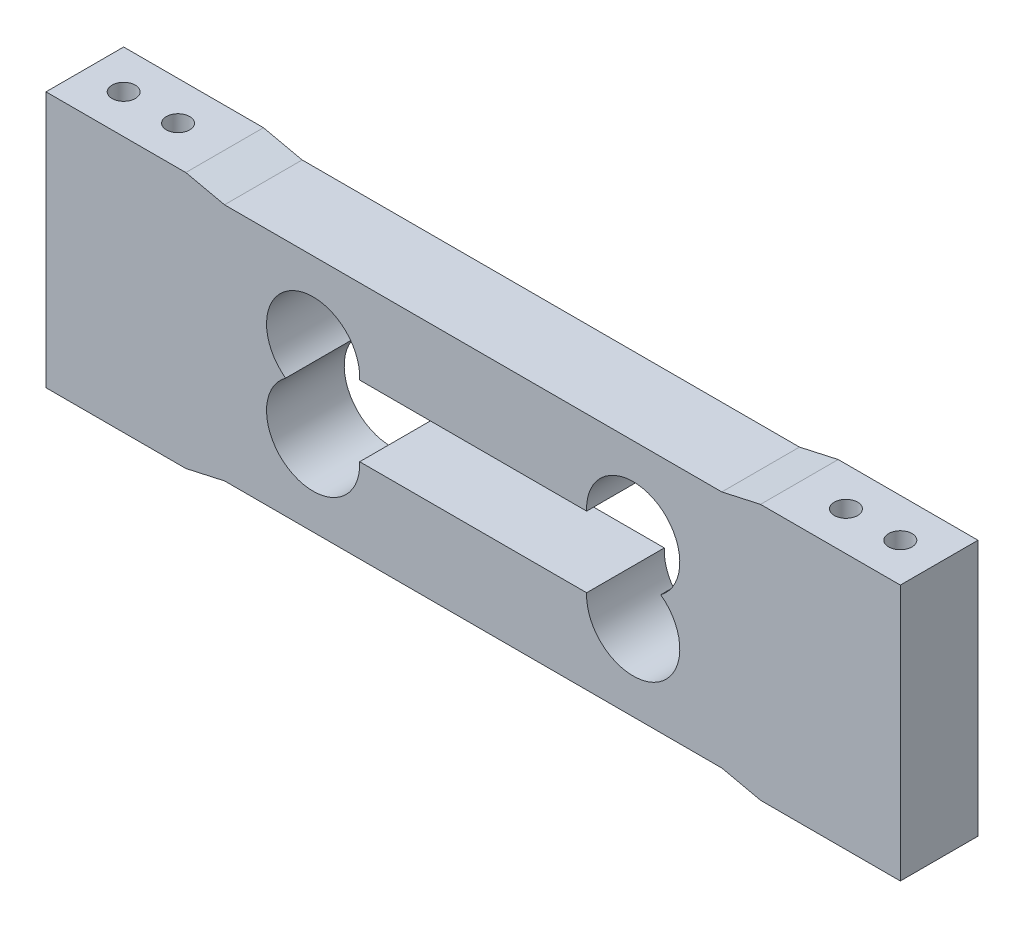
SolidWorks part; units mm, degrees
ref_plane "Front Plane" through (0, 0, 0) normal (0, 0, 1) x (1, 0, 0)
ref_plane "Top Plane" through (0, 0, 0) normal (0, 1, 0) x (1, 0, 0)
ref_plane "Right Plane" through (0, 0, 0) normal (1, 0, 0) x (0, 0, -1)
sketch "Sketch1" plane through (0, 0, 0) normal (0, 0, 1) x (1, 0, 0)
  line L0 (-55, 16.5) -> (-37, 16.5)
  line L1 (-37, 16.5) -> (-32.0158, 15.3954)
  line L2 (-32.0158, 15.3954) -> (32.0158, 15.3954)
  line L3 (32.0158, 15.3954) -> (37, 16.5)
  line L4 (37, 16.5) -> (55, 16.5)
  line L5 (55, 16.5) -> (55, -16.5)
  line L6 (55, -16.5) -> (37, -16.5)
  line L7 (37, -16.5) -> (32.0158, -15.3954)
  line L8 (32.0158, -15.3954) -> (-32.0158, -15.3954)
  line L9 (-32.0158, -15.3954) -> (-37, -16.5)
  line L10 (-37, -16.5) -> (-55, -16.5)
  line L11 (-55, -16.5) -> (-55, 16.5)
  line L12 (0, 15.3954) -> (0, -15.3954) construction
  line L13 (-55, 0) -> (55, 0) construction
  line L14 (-14.6102, 4.5503) -> (14.6102, 4.5503)
  line L15 (-14.6102, -4.5503) -> (14.6102, -4.5503)
  arc A0 (14.6102, 4.5503) -> (24.1514, 0) centre (20.6033, 4.8385) cw
  arc A1 (14.6102, -4.5503) -> (24.1514, 0) centre (20.6033, -4.8385) ccw
  arc A2 (-14.6102, -4.5503) -> (-24.1514, 0) centre (-20.6033, -4.8385) cw
  arc A3 (-14.6102, 4.5503) -> (-24.1514, 0) centre (-20.6033, 4.8385) ccw
  point P14 (0, 0)
  point P20 (-20.3383, 0)
  point P21 (-14.2938, -9.1795)
  point P24 (0, 4.5503)
  point P30 (0, -4.5503)
  point P31 (-20.6262, 0)
  point P32 (-16.8843, -9.947)
  point P33 (0, 0)
  point P34 (-10.456, 7.8988)
  point P36 (0, 3.6258)
  point P37 (14.6102, 4.8385)
  dimension "D1" = 33
  dimension "D2" = 18
  dimension "D3" = 74
  dimension "D4" = 110
extrude "Boss-Extrude1" add sketch "Sketch1" along normal mid plane 10
sketch "Sketch3" plane through (0, 16.5, 0) normal (0, 1, 0) x (1, 0, 0)
  line L0 (-55, 0) -> (55, 0) construction
  line L1 (-55, -5) -> (-55, 5) construction
  line L2 (55, -5) -> (55, 5) construction
  circle A0 centre (-50, 0) radius 1.5
  circle A1 centre (-43, 0) radius 1.5
  circle A2 centre (43, 0) radius 1.5
  circle A3 centre (50, 0) radius 1.5
  point P14 (0, 0)
  point P15 (0, 0)
  point P16 (0, 0)
  point P17 (0, 0)
  dimension "D1" = 3
  dimension "D2" = 3
  dimension "D3" = 3
  dimension "D4" = 3
  dimension "D5" = 5
  dimension "D6" = 7
  dimension "D7" = 7
  dimension "D8" = 86
extrude "Cut-Extrude1" cut sketch "Sketch3" against normal through all
